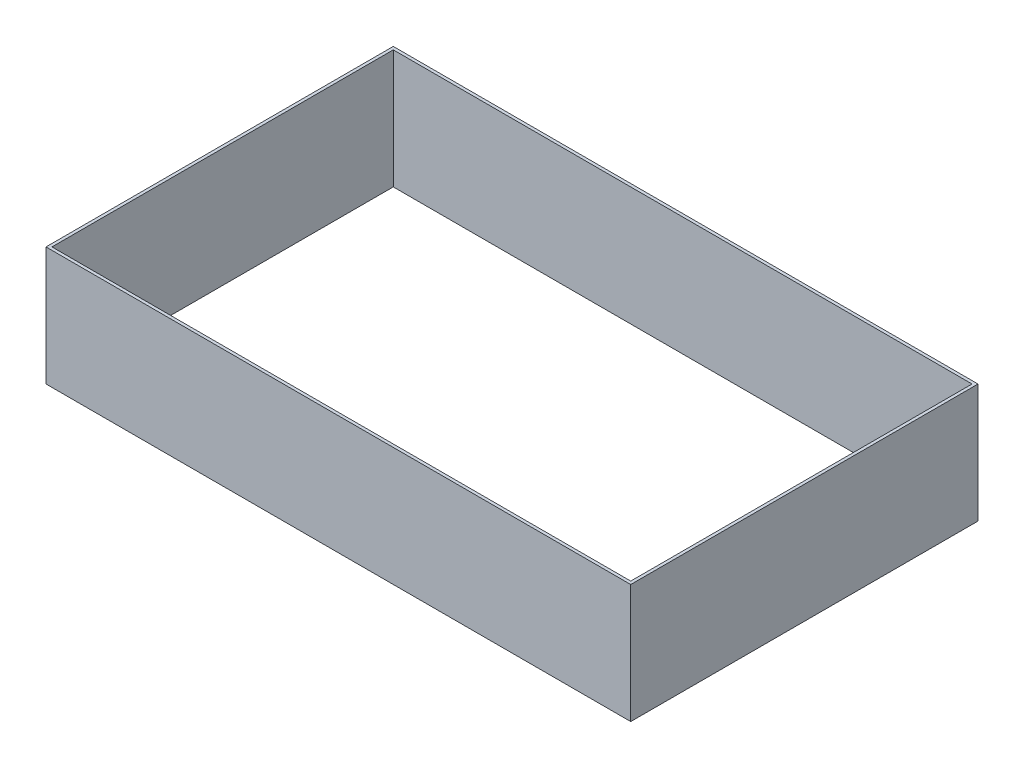
SolidWorks part; units mm, degrees
ref_plane "Front Plane" through (0, 0, 0) normal (0, 0, 1) x (1, 0, 0)
ref_plane "Top Plane" through (0, 0, 0) normal (0, 1, 0) x (1, 0, 0)
ref_plane "Right Plane" through (0, 0, 0) normal (1, 0, 0) x (0, 0, -1)
sketch "Sketch2" plane through (0, 0, 0) normal (0, 1, 0) x (1, 0, 0)
  line L1 (-975, 575) -> (975, 575)
  line L2 (-975, 575) -> (-975, -575)
  line L3 (-975, -575) -> (975, -575)
  line L4 (975, 575) -> (975, -575)
  line L5 (-975, 575) -> (975, -575) construction
  line L6 (-975, -575) -> (975, 575) construction
  point P0 (0, 0)
  dimension "D1" = 1150
  dimension "D2" = 1950
extrude "Extrude-Thin1" add sketch "Sketch2" along normal blind 400 thin thin type one direction wall 10
